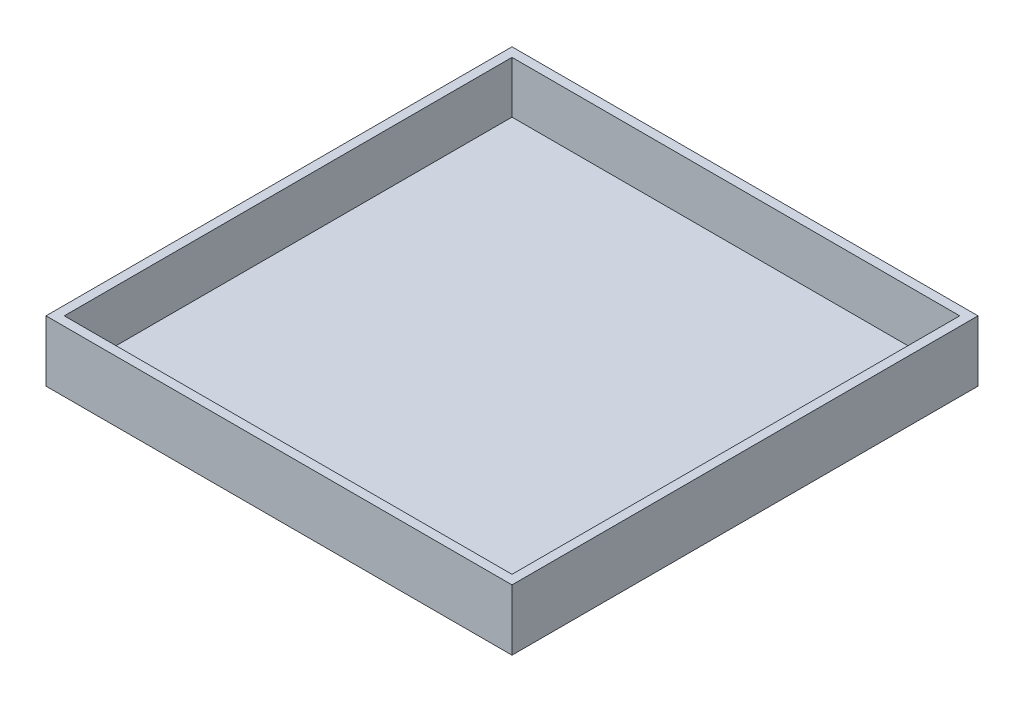
SolidWorks part; units mm, degrees
ref_plane "前视基准面" through (0, 0, 0) normal (0, 0, 1) x (1, 0, 0)
ref_plane "上视基准面" through (0, 0, 0) normal (0, 1, 0) x (1, 0, 0)
ref_plane "右视基准面" through (0, 0, 0) normal (1, 0, 0) x (0, 0, -1)
other "Configuration Table"
sketch "草图1" plane through (0, 0, 0) normal (0, 1, 0) x (1, 0, 0)
  line L1 (-76.5, 76.5) -> (76.5, 76.5)
  line L2 (-76.5, 76.5) -> (-76.5, -76.5)
  line L3 (-76.5, -76.5) -> (76.5, -76.5)
  line L4 (76.5, 76.5) -> (76.5, -76.5)
  line L5 (-76.5, 76.5) -> (76.5, -76.5) construction
  line L6 (-76.5, -76.5) -> (76.5, 76.5) construction
  point P0 (0, 0)
  dimension "D1" = 153
  dimension "D2" = 153
extrude "凸台-拉伸1" add sketch "草图1" along normal blind 20
shell "抽壳1" thickness 3
